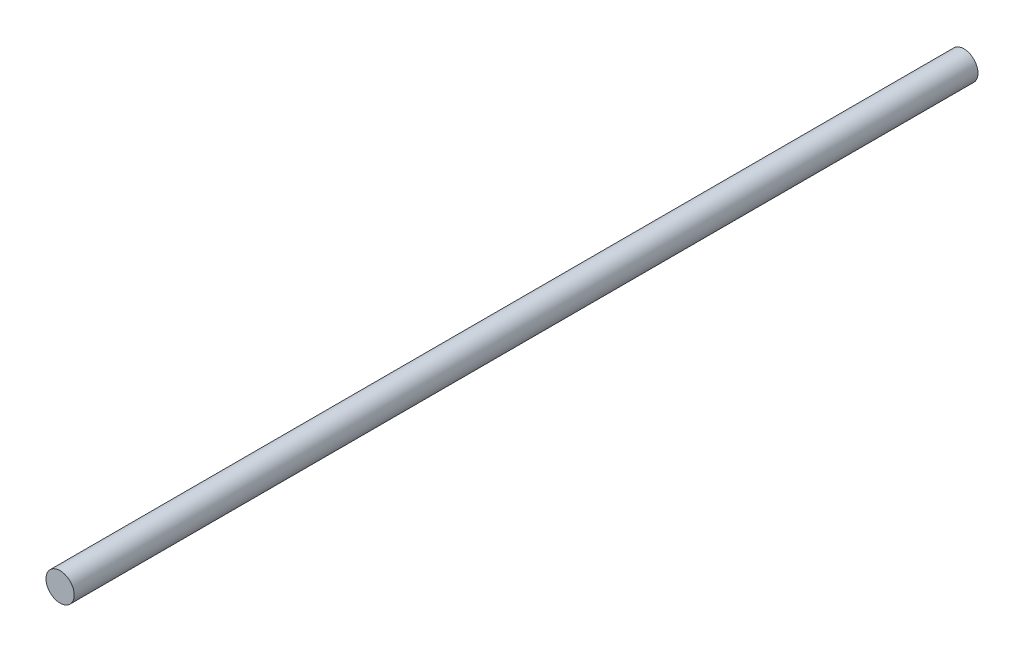
SolidWorks part; units mm, degrees
ref_plane "Front Plane" through (0, 0, 0) normal (0, 0, 1) x (1, 0, 0)
ref_plane "Top Plane" through (0, 0, 0) normal (0, 1, 0) x (1, 0, 0)
ref_plane "Right Plane" through (0, 0, 0) normal (1, 0, 0) x (0, 0, -1)
sketch "Sketch1" plane through (0, 0, 0) normal (0, 1, 0) x (1, 0, 0)
  line L0 (0, 0) -> (0, 162.814)
  dimension "D1" = 162.814
sketch "Sketch2" plane through (0, 0, 0) normal (0, 0, 1) x (1, 0, 0)
  circle A0 centre (0, 0) radius 2.54
  dimension "D1" = 5.08
sweep "Sweep3" add profiles "Sketch2" path "Sketch1"
